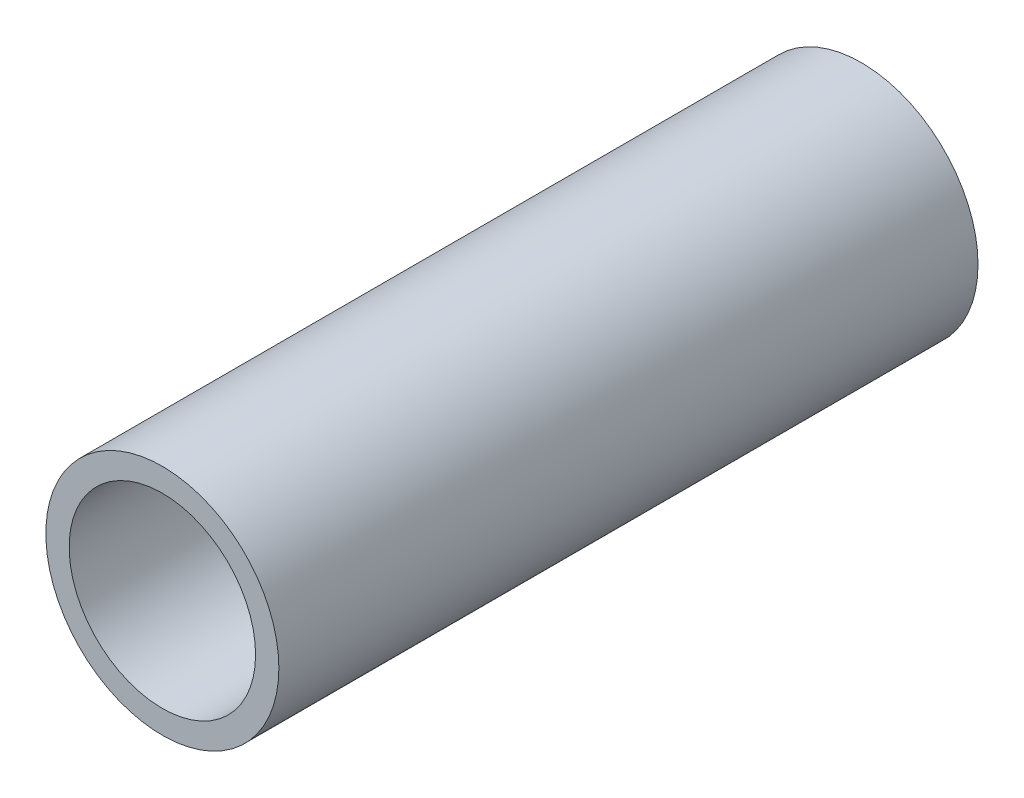
SolidWorks part; units mm, degrees
ref_plane "Front Plane" through (0, 0, 0) normal (0, 0, 1) x (1, 0, 0)
ref_plane "Top Plane" through (0, 0, 0) normal (0, 1, 0) x (1, 0, 0)
ref_plane "Right Plane" through (0, 0, 0) normal (1, 0, 0) x (0, 0, -1)
sketch "Sketch2" plane through (0, 0, 0) normal (0, 0, 1) x (1, 0, 0)
  circle A0 centre (0, 0) radius 5
  circle A1 centre (0, 0) radius 4
  dimension "D1" = 10
  dimension "D2" = 8
extrude "Boss-Extrude1" add sketch "Sketch2" along normal blind 30
